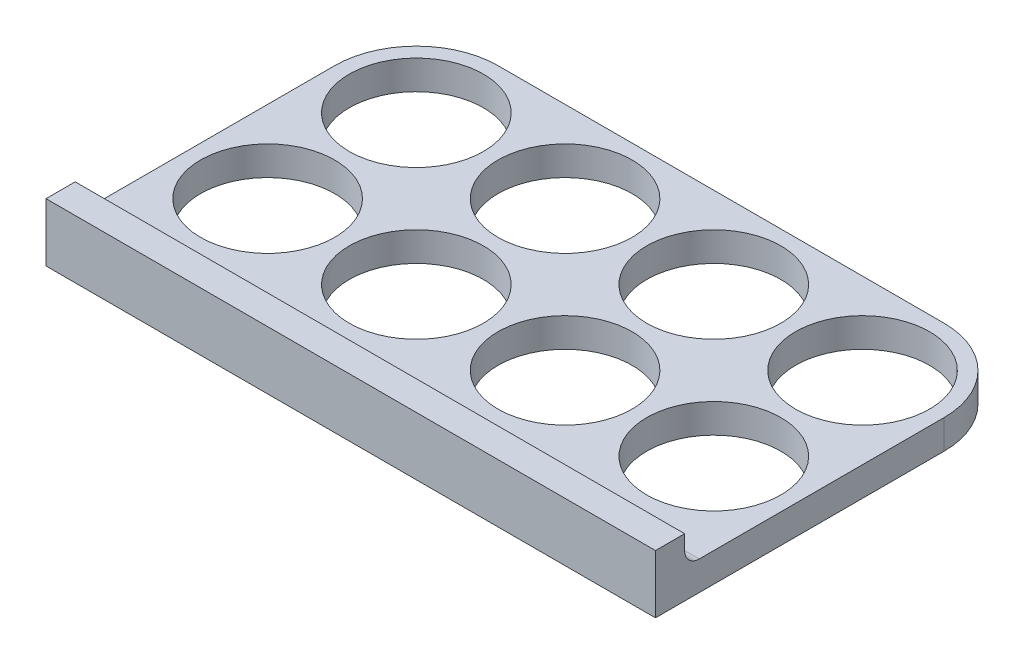
SolidWorks part; units mm, degrees
ref_plane "Front Plane" through (0, 0, 0) normal (0, 0, 1) x (1, 0, 0)
ref_plane "Top Plane" through (0, 0, 0) normal (0, 1, 0) x (1, 0, 0)
ref_plane "Right Plane" through (0, 0, 0) normal (1, 0, 0) x (0, 0, -1)
sketch "Sketch1" plane through (0, 0, 0) normal (0, 1, 0) x (1, 0, 0)
  line L0 (0, 20.4) -> (20.4, 20.4) construction
  line L1 (20.4, 20.4) -> (40.8, 20.4) construction
  line L2 (40.8, 20.4) -> (61.2, 20.4) construction
  line L3 (-11.2, 20.4) -> (-11.2, -19.2)
  line L4 (-11.2, -19.2) -> (72.4, -19.2)
  line L5 (72.4, -19.2) -> (72.4, 20.4)
  line L6 (0, 31.6) -> (61.2, 31.6)
  line L7 (0, -9.2) -> (61.2, -9.2) construction
  circle A0 centre (0, 0) radius 9.2
  circle A1 centre (20.4, 0) radius 9.2
  circle A2 centre (40.8, 0) radius 9.2
  circle A3 centre (61.2, 0) radius 9.2
  circle A4 centre (20.4, 20.4) radius 9.2
  circle A5 centre (40.8, 20.4) radius 9.2
  circle A6 centre (61.2, 20.4) radius 9.2
  circle A7 centre (0, 20.4) radius 9.2
  arc A8 (0, 31.6) -> (-11.2, 20.4) centre (0, 20.4) ccw
  arc A9 (72.4, 20.4) -> (61.2, 31.6) centre (61.2, 20.4) ccw
  point P19 (0, 29.6)
  point P24 (0, -9.2)
  point P25 (61.2, 29.6)
  point P26 (61.2, 31.6)
  point P27 (61.2, -9.2)
  dimension "D1" = 18.4
  dimension "D2" = 4
  dimension "D5" = 2
  dimension "D4" = 20.4
  dimension "D6" = 2
  dimension "D7" = 10
  dimension "D3" = 2
extrude "Boss-Extrude1" add sketch "Sketch1" along normal blind 4
sketch "Sketch2" plane through (0, 4, 0) normal (0, 1, 0) x (1, 0, 0)
  line L0 (-11.2, -19.2) -> (72.4, -19.2) construction
  line L1 (-11.2, -19.2) -> (72.4, -19.2)
  line L2 (-11.2, 20.4) -> (-11.2, -19.2) construction
  line L3 (-11.2, 20.4) -> (-11.2, -19.2)
  line L4 (72.4, -19.2) -> (72.4, 20.4) construction
  line L5 (72.4, -19.2) -> (72.4, 20.4)
  line L6 (-11.2, -15.2) -> (72.4, -15.2)
  line M9 (-11.2, -19.2) -> (72.4, -19.2)
  line M10 (72.4, -19.2) -> (72.4, 20.4)
  dimension "D1" = 4
extrude "Boss-Extrude2" add sketch "Sketch2" along normal blind 4 contours L6 L3 M9 M10
fillet "Fillet1" radius 2 1 edges at (30.6, 4, 15.2)
